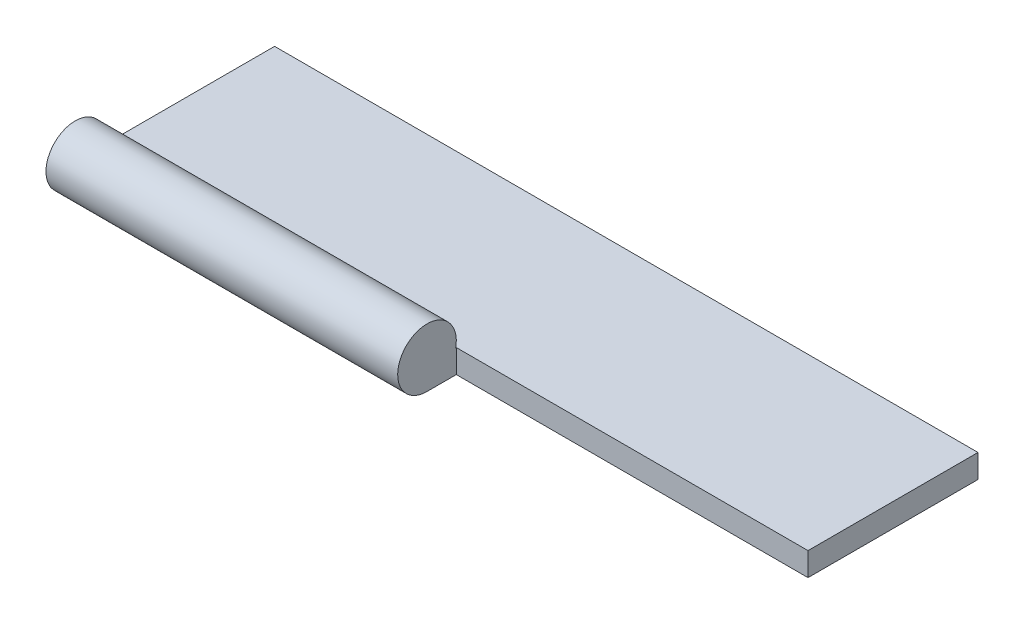
SolidWorks part; units mm, degrees
ref_plane "Front Plane" through (0, 0, 0) normal (0, 0, 1) x (1, 0, 0)
ref_plane "Top Plane" through (0, 0, 0) normal (0, 1, 0) x (1, 0, 0)
ref_plane "Right Plane" through (0, 0, 0) normal (1, 0, 0) x (0, 0, -1)
sketch "Sketch1" plane through (0, 0, 0) normal (1, 0, 0) x (0, 0, -1)
  line L0 (0, -2.5) -> (17, -2.5)
  line L1 (17, -2.5) -> (17, -0.5)
  line L2 (17, -0.5) -> (2.4495, -0.5)
  arc A0 (2.4495, -0.5) -> (0, -2.5) centre (0, 0) ccw
  dimension "D1" = 5
  dimension "D2" = 17
  dimension "D3" = 2
extrude "Boss-Extrude1" add sketch "Sketch1" along normal blind 60
sketch "Sketch3" plane through (0, -2.5, 0) normal (0, -1, 0) x (1, 0, 0)
  line L0 (60, 0) -> (0, 0) construction
  line L1 (60, 0) -> (0, 0) construction
  line L2 (30, 2.5) -> (30, -2.5)
  line L3 (30, -2.5) -> (61.6914, -2.5)
  line L4 (61.6914, -2.5) -> (61.6914, 2.5)
  line L5 (61.6914, 2.5) -> (30, 2.5)
  line L6 (60, 0) -> (60, -17) construction
  point P5 (30, 0)
  dimension "D1" = 2.5
  dimension "D2" = 30
extrude "Cut-Extrude1" cut sketch "Sketch3" against normal through all
